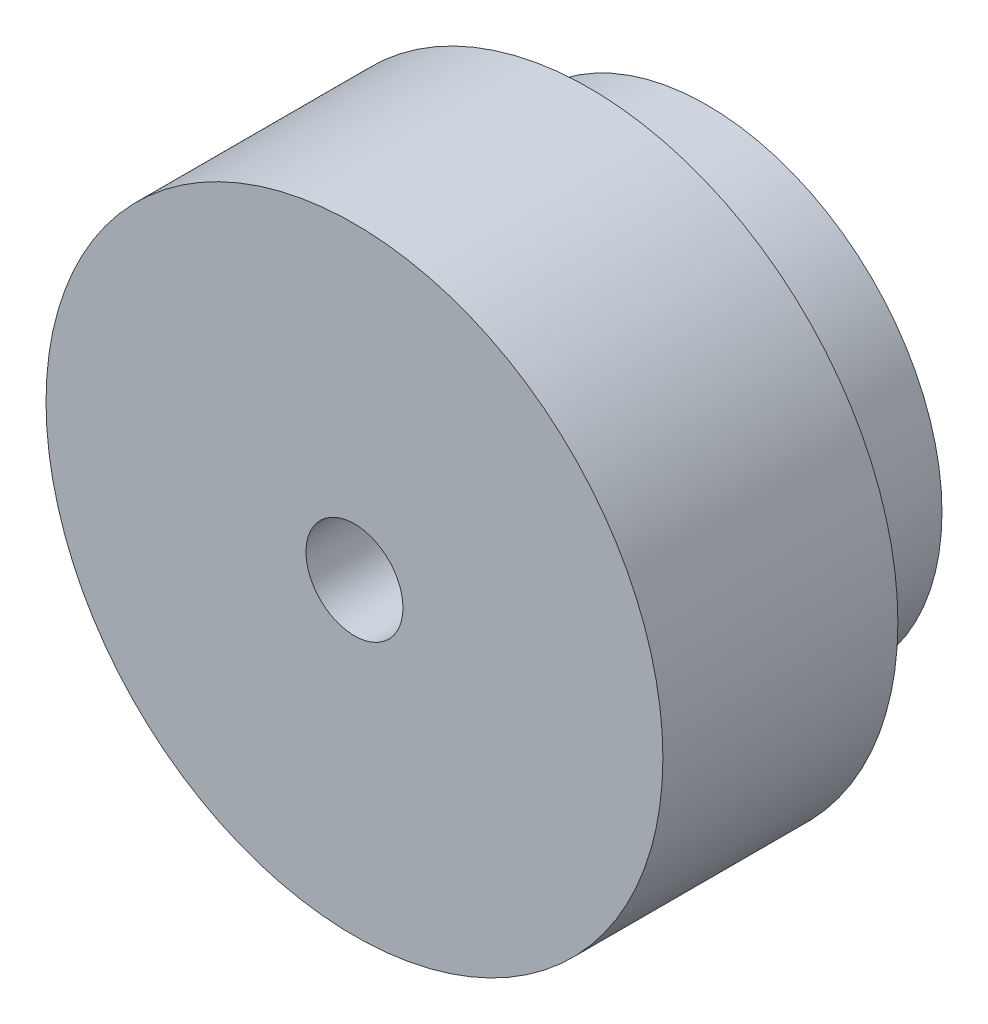
SolidWorks part; units mm, degrees
ref_plane "Front Plane" through (0, 0, 0) normal (0, 0, 1) x (1, 0, 0)
ref_plane "Top Plane" through (0, 0, 0) normal (0, 1, 0) x (1, 0, 0)
ref_plane "Right Plane" through (0, 0, 0) normal (1, 0, 0) x (0, 0, -1)
sketch "Sketch1" plane through (0, 0, 0) normal (1, 0, 0) x (0, 0, -1)
  line L0 (0, 3.302) -> (-24, 3.302)
  line L1 (-24, 3.302) -> (-24, 21)
  line L2 (-24, 21) -> (-8, 21)
  line L3 (-8, 21) -> (-8, 16.002)
  line L4 (-8, 16.002) -> (0, 16.002)
  line L5 (0, 16.002) -> (0, 3.302)
  line L6 (0, 0) -> (18.7234, 0) construction
  dimension "D1" = 3.302
  dimension "D2" = 21
  dimension "D3" = 16
  dimension "D4" = 8
  dimension "D5" = 12.7
revolve "Revolve1" add sketch "Sketch1" angle 360 about L6
